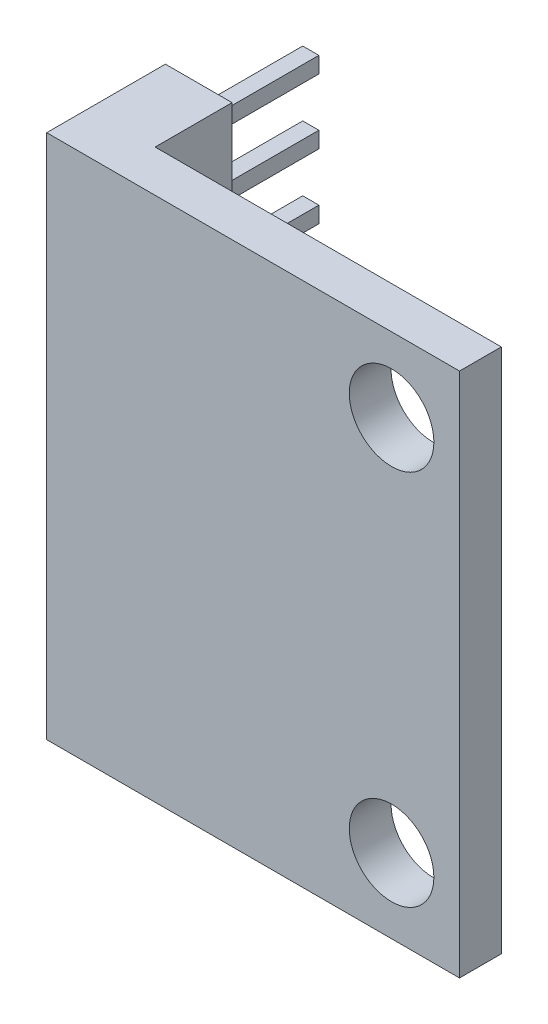
SolidWorks part; units mm, degrees
ref_plane "Front Plane" through (0, 0, 0) normal (0, 0, 1) x (1, 0, 0)
ref_plane "Top Plane" through (0, 0, 0) normal (0, 1, 0) x (1, 0, 0)
ref_plane "Right Plane" through (0, 0, 0) normal (1, 0, 0) x (0, 0, -1)
sketch "Sketch1" plane through (0, 0, 0) normal (0, 0, 1) x (1, 0, 0)
  line L1 (8.05, -10.25) -> (-8.05, -10.25)
  line L2 (8.05, -10.25) -> (8.05, 10.25)
  line L3 (8.05, 10.25) -> (-8.05, 10.25)
  line L4 (-8.05, -10.25) -> (-8.05, 10.25)
  line L5 (8.05, -10.25) -> (-8.05, 10.25) construction
  line L6 (8.05, 10.25) -> (-8.05, -10.25) construction
  point P0 (0, 0)
  dimension "D1" = 20.5
  dimension "D2" = 16.1
extrude "Boss-Extrude1" add sketch "Sketch1" along normal blind 1.63
sketch "Sketch2" plane through (0, 0, 1.63) normal (0, 0, 1) x (1, 0, 0)
  line L0 (5.4, 7.35) -> (5.4, 10.25) construction
  line L1 (8.05, 10.25) -> (-8.05, 10.25) construction
  line L2 (5.4, 7.35) -> (8.05, 7.35) construction
  line L3 (8.05, -10.25) -> (8.05, 10.25) construction
  line L4 (0, 0) -> (8.05, 0) construction
  circle A0 centre (5.4, 7.35) radius 1.65
  circle A2 centre (5.4, -7.35) radius 1.65
  point P4 (7.05, 7.35)
  point P11 (5.4, 9)
  dimension "D1" = 3.3
  dimension "D2" = 14.7
  dimension "D3" = 1
extrude "Cut-Extrude1" cut sketch "Sketch2" against normal through all both and the other way through all
sketch "Sketch3" plane through (0, 0, 0) normal (0, 0, -1) x (-1, 0, 0)
  line L0 (8.05, -10.25) -> (-8.05, -10.25) construction
  line L1 (8.05, 10.25) -> (5.45, 10.25)
  line L2 (8.05, 10.25) -> (8.05, -10.25)
  line L3 (8.05, -10.25) -> (5.45, -10.25)
  line L4 (5.45, 10.25) -> (5.45, -10.25)
  line L5 (6.75, -10.25) -> (6.75, 10.25) construction
  line L6 (8.05, 0) -> (5.45, 0) construction
  point P148 (6.75, 0)
  dimension "D1" = 2.6
extrude "Boss-Extrude2" add sketch "Sketch3" along normal blind 3
sketch "Sketch4" plane through (0, 0, -3) normal (0, 0, -1) x (-1, 0, 0)
  line L0 (6.75, 9.17) -> (6.75, 10.25) construction
  line L1 (7.065, 9.17) -> (6.435, 9.17)
  line L2 (7.065, 9.17) -> (7.065, 8.54)
  line L3 (7.065, 8.54) -> (6.435, 8.54)
  line L4 (6.435, 9.17) -> (6.435, 8.54)
  line L5 (6.75, 8.54) -> (6.75, 9.17) construction
  line L6 (7.065, 8.855) -> (6.435, 8.855) construction
  line L9 (0, 0) -> (6.75, 0) construction
  line L10 (7.065, 6.64) -> (7.065, 6.01)
  line L11 (7.065, 6.64) -> (6.435, 6.64)
  line L12 (6.435, 6.64) -> (6.435, 6.01)
  line L13 (7.065, 6.01) -> (6.435, 6.01)
  line L14 (7.065, 4.11) -> (7.065, 3.48)
  line L15 (7.065, 4.11) -> (6.435, 4.11)
  line L16 (6.435, 4.11) -> (6.435, 3.48)
  line L17 (7.065, 3.48) -> (6.435, 3.48)
  line L18 (7.065, 1.58) -> (7.065, 0.95)
  line L19 (7.065, 1.58) -> (6.435, 1.58)
  line L20 (6.435, 1.58) -> (6.435, 0.95)
  line L21 (7.065, 0.95) -> (6.435, 0.95)
  line L22 (7.065, -0.95) -> (7.065, -1.58)
  line L23 (7.065, -0.95) -> (6.435, -0.95)
  line L24 (6.435, -0.95) -> (6.435, -1.58)
  line L25 (7.065, -1.58) -> (6.435, -1.58)
  line L26 (7.065, -3.48) -> (7.065, -4.11)
  line L27 (7.065, -3.48) -> (6.435, -3.48)
  line L28 (6.435, -3.48) -> (6.435, -4.11)
  line L29 (7.065, -4.11) -> (6.435, -4.11)
  line L30 (7.065, -6.01) -> (7.065, -6.64)
  line L31 (7.065, -6.01) -> (6.435, -6.01)
  line L32 (6.435, -6.01) -> (6.435, -6.64)
  line L33 (7.065, -6.64) -> (6.435, -6.64)
  line L34 (7.065, -8.54) -> (7.065, -9.17)
  line L35 (7.065, -8.54) -> (6.435, -8.54)
  line L36 (6.435, -8.54) -> (6.435, -9.17)
  line L37 (7.065, -9.17) -> (6.435, -9.17)
  line L38 (6.75, 0.95) -> (6.75, -0.95) construction
  line L39 (8.05, 10.25) -> (5.45, 10.25) construction
  point P4 (6.75, 0)
  point P132 (6.75, 8.855)
  dimension "D1" = 0.63
  dimension "D3" = 2.53
  dimension "D2" = 8
extrude "Boss-Extrude3" add sketch "Sketch4" along normal offset from surface (4.37 mm away) 9 up to face at (7.05, 7.35, 1.63)
